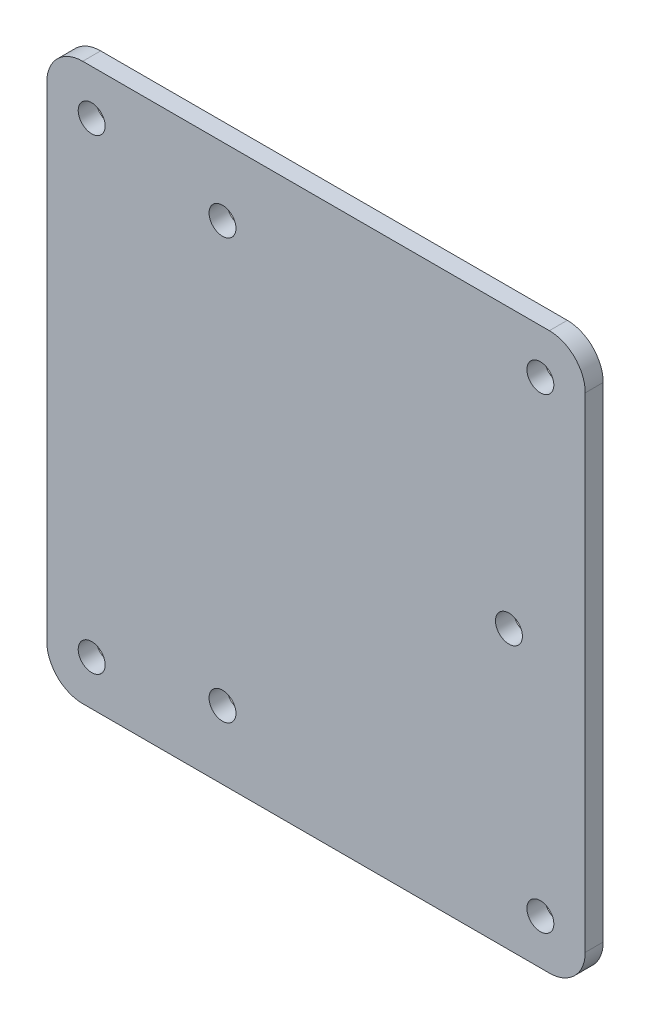
SolidWorks part; units mm, degrees
ref_plane "Alzado" through (0, 0, 0) normal (0, 0, 1) x (1, 0, 0)
ref_plane "Planta" through (0, 0, 0) normal (0, 1, 0) x (1, 0, 0)
ref_plane "Vista lateral" through (0, 0, 0) normal (1, 0, 0) x (0, 0, -1)
sketch "Croquis1" plane through (0, 0, 0) normal (0, 0, 1) x (1, 0, 0)
  line L0 (30, 31) -> (-30, 31)
  line L1 (25, -26) -> (23.5, -26)
  line L2 (25, -26) -> (25, -24.5)
  line L3 (25, 26) -> (23.5, 26)
  line L4 (-25, -26) -> (-25, -24.5)
  line L5 (25, -26) -> (23.9603, -24.9188) construction
  line L6 (25, 26) -> (23.9603, 24.9188) construction
  line L7 (-30, -31) -> (-30, 31)
  line L8 (30, -31) -> (-30, -31)
  line L9 (30, -31) -> (30, 31)
  line L10 (-25, 24.5) -> (-25, 26)
  line L11 (-25, -26) -> (-25, 26) construction
  line L12 (-23.9603, 24.9188) -> (-25, 26) construction
  line L13 (-23.5, 26) -> (-25, 26)
  line L14 (25, 26) -> (-25, 26) construction
  line L15 (-23.9603, -24.9188) -> (-25, -26) construction
  line L16 (25, 24.5) -> (25, 26)
  line L17 (25, -26) -> (25, 26) construction
  line L18 (-23.5, -26) -> (-25, -26)
  line L19 (25, -26) -> (-25, -26) construction
  circle A0 centre (-25, 26) radius 1.5
  circle A1 centre (25, 26) radius 1.5
  circle A2 centre (25, -26) radius 1.5
  circle A3 centre (-25, -26) radius 1.5
  point P0 (0, 0)
  dimension "D4" = 3
  dimension "D1" = 50
  dimension "D2" = 52
  dimension "D3" = 5
extrude "Saliente-Extruir1" add sketch "Croquis1" along normal blind 2 contours L8 L9 L0 L7 A3 A2 A1 A0
fillet "Redondeo1" radius 4 4 edges at (-30, -31, 1) (-30, 31, 1) (30, 31, 1) (30, -31, 1)
sketch "Croquis3" plane through (0, 0, 2) normal (0, 0, 1) x (1, 0, 0)
  line L0 (0, 0) -> (21.5, 0) construction
  line L1 (26, -31) -> (-26, -31) construction
  line L2 (0, -31) -> (0, 31) construction
  line L3 (26, 31) -> (-26, 31) construction
  line L4 (0, 0) -> (-10.42, 0) construction
  line L5 (-10.42, -23.4) -> (-10.42, 23.4) construction
  circle A3 centre (-10.42, 23.4) radius 1.5
  circle A4 centre (-10.42, -23.4) radius 1.5
  circle A5 centre (21.5, 0) radius 1.5
  point P10 (0, 10.4168)
  point P19 (0, 0)
  point P22 (-10.42, 0)
  dimension "D2" = 31.92
  dimension "D3" = 3
  dimension "D9" = 3
  dimension "D10" = 3
  dimension "D7" = 10.42
  dimension "D8" = 23.4
extrude "Cortar-Extruir1" cut sketch "Croquis3" against normal blind 2
